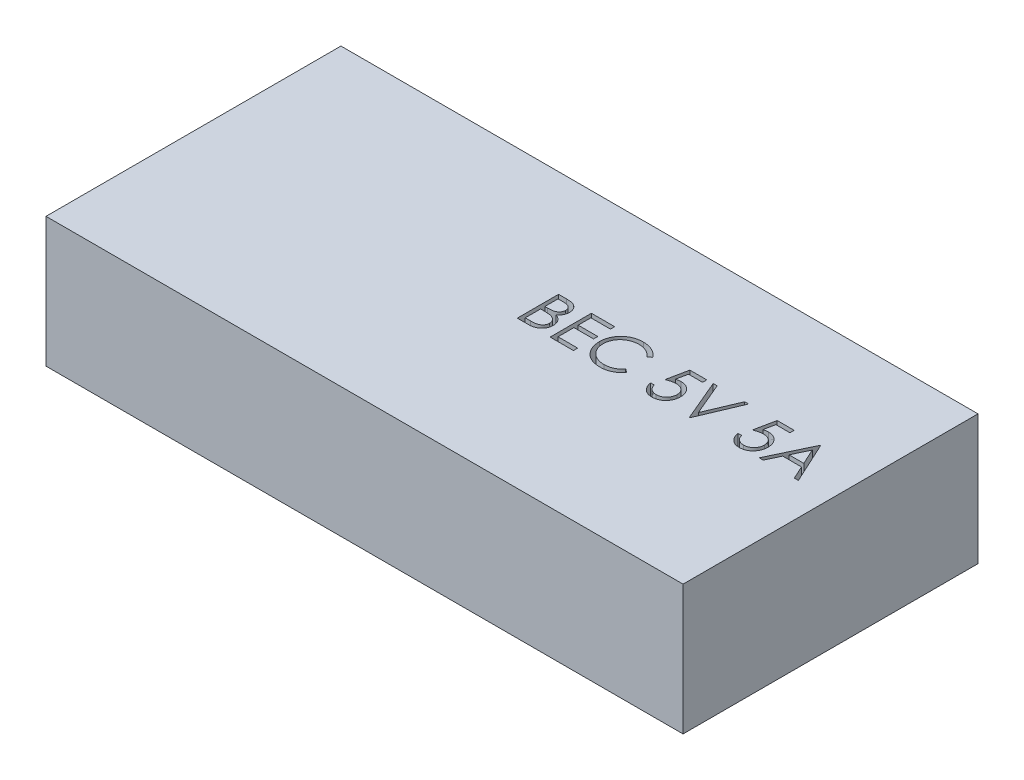
SolidWorks part; units mm, degrees
material "Manual Density from Real Component Mass UBEC & Other Components"
ref_plane "Piano frontale" through (0, 0, 0) normal (0, 0, 1) x (1, 0, 0)
ref_plane "Piano superiore" through (0, 0, 0) normal (0, 1, 0) x (1, 0, 0)
ref_plane "Piano destro" through (0, 0, 0) normal (1, 0, 0) x (0, 0, -1)
sketch "Schizzo1" plane through (0, 0, 0) normal (0, 1, 0) x (1, 0, 0)
  line L1 (-27, -12.5) -> (27, -12.5)
  line L2 (-27, -12.5) -> (-27, 12.5)
  line L3 (-27, 12.5) -> (27, 12.5)
  line L4 (27, -12.5) -> (27, 12.5)
  line L5 (-27, -12.5) -> (27, 12.5) construction
  line L6 (-27, 12.5) -> (27, -12.5) construction
  point P0 (0, 0)
  dimension "D1" = 54
  dimension "D2" = 25
extrude "Estrusione-Estrusione1" add sketch "Schizzo1" along normal blind 11
sketch "Schizzo2" plane through (0, 11, 0) normal (0, 1, 0) x (1, 0, 0)
  text T0 "BEC 5V 5A"
extrude "Taglio-Estrusione1" cut sketch "Schizzo2" against normal blind 2
